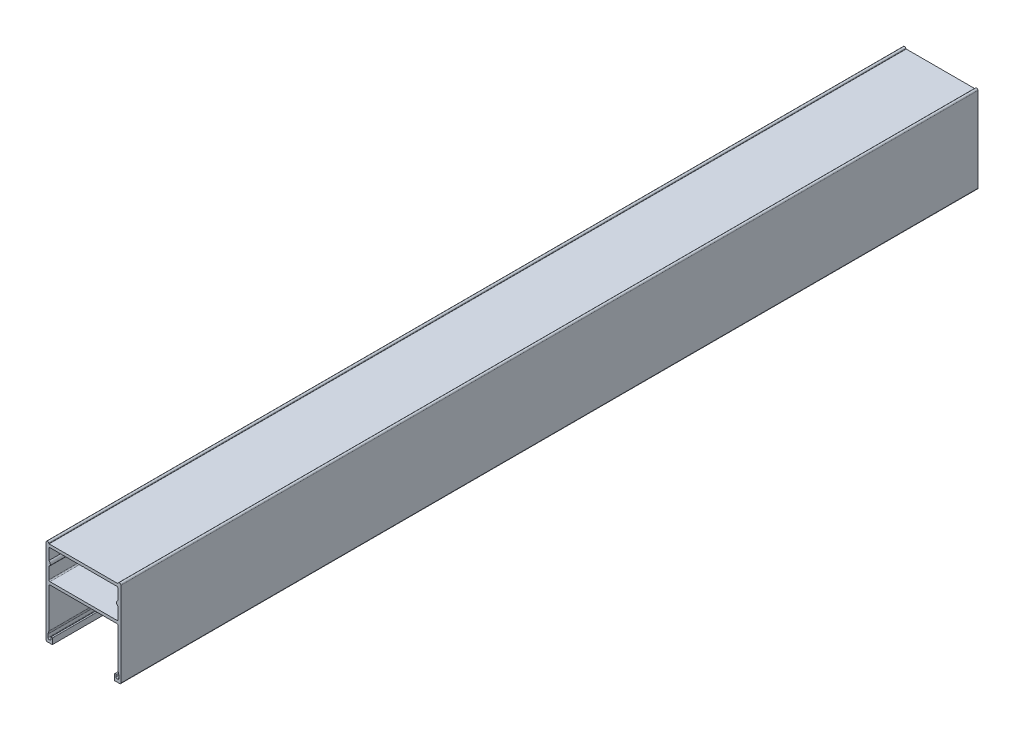
SolidWorks part; units mm, degrees
material "6063-T6"
ref_plane "Front Plane" through (0, 0, 0) normal (0, 0, 1) x (1, 0, 0)
ref_plane "Top Plane" through (0, 0, 0) normal (0, 1, 0) x (1, 0, 0)
ref_plane "Right Plane" through (0, 0, 0) normal (1, 0, 0) x (0, 0, -1)
sketch "Sketch1" plane through (0, 0, 0) normal (0, 0, 1) x (1, 0, 0)
  line L0 (-12.1, 28.6) -> (-12.1, 24.8899)
  line L1 (-12.0084, 30) -> (12.0084, 30)
  line L2 (-13.1, 30) -> (-13.1, 17.7)
  line L3 (-11.7, 17.7) -> (11.7, 17.7)
  line L4 (13.1, 30) -> (13.1, 17.7)
  line L5 (-13.1, 30) -> (13.1, 17.7) construction
  line L6 (-13.1, 17.7) -> (13.1, 30) construction
  line L7 (-11.7, 18.7) -> (11.7, 18.7)
  line L8 (12.1, 28.6) -> (12.1, 24.8899)
  line L9 (-11.7, 29) -> (-0.1732, 29)
  line L10 (0, 0) -> (0, 28.7113) construction
  line L11 (0, -55) -> (0, 55) construction
  line L12 (-13.1, 30) -> (13.1, 30) construction
  line L13 (-12.1, 29) -> (-12.1, 18.7) construction
  line L14 (-12.1, 18.7) -> (12.1, 18.7) construction
  line L15 (12.1, 29) -> (12.1, 18.7) construction
  line L16 (-12.1, 29) -> (12.1, 29) construction
  line L17 (-12.3804, 2.5557) -> (-12.1166, 3.4443)
  line L19 (-13.1, 17.7) -> (-13.1, 0.4)
  line L21 (-12.1, 17.3) -> (-12.1, 3.5581)
  line L25 (-12.397, 2.4419) -> (-12.397, 1.4)
  line L26 (-13.1, 17.7) -> (13.1, 17.7) construction
  line L29 (-12.7, 0) -> (-10.9, 0)
  line L31 (-11.997, 1) -> (-11.797, 1)
  line L34 (-10.9, 0) -> (-10.9, 2)
  line L36 (-11.397, 1.4) -> (-11.397, 2)
  line L37 (11.397, 1.4) -> (11.397, 2)
  line L38 (10.9, 0) -> (10.9, 2)
  line L41 (11.997, 1) -> (11.797, 1)
  line L43 (12.7, 0) -> (10.9, 0)
  line L46 (12.397, 2.4419) -> (12.397, 1.4)
  line L49 (12.1, 17.3) -> (12.1, 3.5581)
  line L51 (13.1, 17.7) -> (13.1, 0.4)
  line L52 (12.3804, 2.5557) -> (12.1166, 3.4443)
  line L53 (0, 29) -> (0, 50000) construction
  line L55 (0.1732, 29) -> (0, 29.3)
  line L56 (0, 29.3) -> (-0.1732, 29)
  line L57 (-0.5575, 28.85) -> (-0.0575, 28.85) [skipped]
  line L58 (0.1732, 29) -> (11.7, 29)
  line L59 (-12.1, 23.1578) -> (-12.1, 19.1)
  line L60 (12.1, 23.1578) -> (12.1, 19.1)
  arc A1 (-12.107, 30.0833) -> (-13.1, 30) centre (-12.6, 30) ccw
  arc A2 (12.107, 30.0833) -> (13.1, 30) centre (12.6, 30) cw
  arc A3 (12.0084, 30) -> (12.107, 30.0833) centre (12.0084, 30.1) ccw
  arc A4 (-12.0084, 30) -> (-12.107, 30.0833) centre (-12.0084, 30.1) cw
  arc A5 (-12.1, 19.1) -> (-11.7, 18.7) centre (-11.7, 19.1) ccw
  arc A6 (11.7, 18.7) -> (12.1, 19.1) centre (11.7, 19.1) ccw
  arc A7 (12.1, 28.6) -> (11.7, 29) centre (11.7, 28.6) ccw
  arc A8 (-12.1, 28.6) -> (-11.7, 29) centre (-11.7, 28.6) cw
  arc A9 (-11.397, 2) -> (-10.9, 2) centre (-11.1485, 2) cw
  arc A10 (11.397, 2) -> (10.9, 2) centre (11.1485, 2) ccw
  arc A11 (12.1, 17.3) -> (11.7, 17.7) centre (11.7, 17.3) ccw
  arc A12 (-11.7, 17.7) -> (-12.1, 17.3) centre (-11.7, 17.3) ccw
  arc A13 (0.1, 29) -> (-0.1, 29) centre (0, 29) ccw construction
  arc A15 (-12.1, 24.8899) -> (-12.1, 23.1578) centre (-12.6, 24.0238) cw
  arc A16 (12.1, 24.8899) -> (12.1, 23.1578) centre (12.6, 24.0238) ccw
  arc A17 (12.7, 0) -> (13.1, 0.4) centre (12.7, 0.4) ccw
  arc A18 (-13.1, 0.4) -> (-12.7, 0) centre (-12.7, 0.4) ccw
  arc A19 (-12.1166, 3.4443) -> (-12.1, 3.5581) centre (-12.5, 3.5581) ccw
  arc A20 (12.1, 3.5581) -> (12.1166, 3.4443) centre (12.5, 3.5581) ccw
  arc A21 (12.397, 2.4419) -> (12.3804, 2.5557) centre (11.997, 2.4419) ccw
  arc A22 (11.397, 1.4) -> (11.797, 1) centre (11.797, 1.4) ccw
  arc A23 (11.997, 1) -> (12.397, 1.4) centre (11.997, 1.4) ccw
  arc A24 (-11.397, 1.4) -> (-11.797, 1) centre (-11.797, 1.4) cw
  arc A25 (-11.997, 1) -> (-12.397, 1.4) centre (-11.997, 1.4) cw
  arc A26 (-12.3804, 2.5557) -> (-12.397, 2.4419) centre (-11.997, 2.4419) ccw
  point P0 (0, 23.85)
  point P38 (13.1, 0)
  point P55 (-13.1, 0)
  point P59 (-12.1, 3.5)
  point P66 (12.1, 17.7)
  point P69 (-12.1, 17.7)
  point P87 (12.1, 3.5)
  point P90 (12.397, 2.5)
  point P93 (11.397, 1)
  point P96 (12.397, 1)
  point P99 (-11.397, 1)
  point P102 (-12.397, 1)
  point P105 (-12.397, 2.5)
  dimension "D4" = 17.7
  dimension "D5" = 30
  dimension "D6" = 1
  dimension "D7" = 0.1
  dimension "D8" = 0.4
  dimension "D17" = 0.4
  dimension "D19" = 1
  dimension "D20" = 5.9762
  dimension "D9" = 0.1
  dimension "D12" = 0.4
  dimension "D1" = 12.3
  dimension "D2" = 26.2
  dimension "D10" = 17.7
  dimension "D11" = 0.3
  dimension "D13" = 1
  dimension "D14" = 2
  dimension "D16" = 1
  dimension "D18" = 9.5
  dimension "D3" = 1
extrude "Boss-Extrude1" add sketch "Sketch1" along normal blind 300
